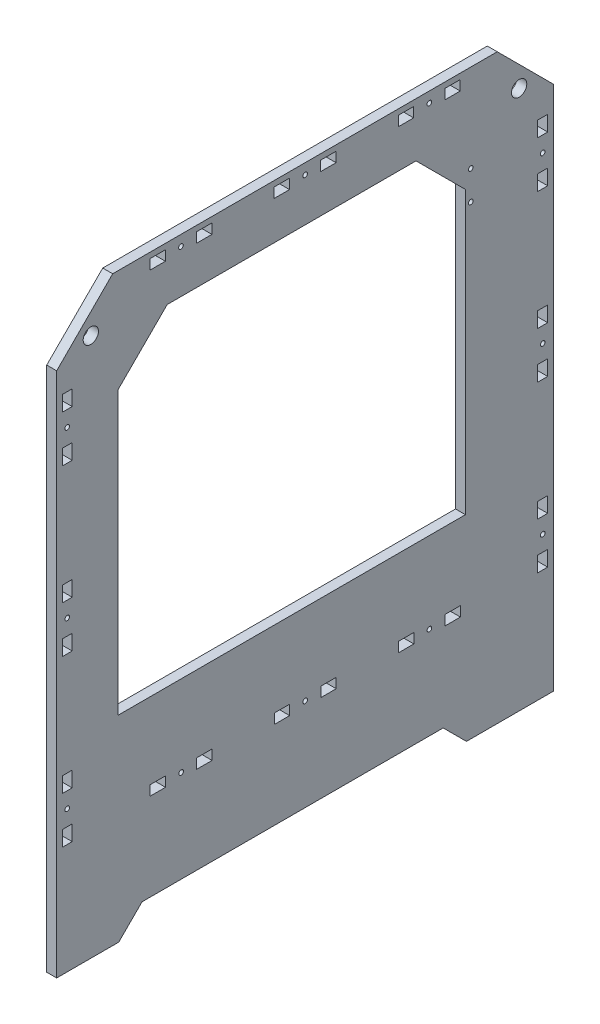
SolidWorks part; units mm, degrees
ref_plane "Front Plane" through (0, 0, 0) normal (0, 0, 1) x (1, 0, 0)
ref_plane "Top Plane" through (0, 0, 0) normal (0, 1, 0) x (1, 0, 0)
ref_plane "Right Plane" through (0, 0, 0) normal (1, 0, 0) x (0, 0, -1)
sketch "Sketch1" plane through (0, 0, 0) normal (1, 0, 0) x (0, 0, -1)
  line L1 (210.165, 41.2752) -> (-37.635, 41.2752)
  line L2 (-8.535, -255.9248) -> (-8.535, -262.3248) construction
  line L3 (181.365, 37.6752) -> (181.365, 31.2752) construction
  line L4 (151.365, 34.4752) -> (181.365, 34.4752) construction
  line L5 (151.465, -259.1248) -> (181.465, -259.1248) construction
  line L6 (71.465, -259.1248) -> (101.465, -259.1248) construction
  line L7 (-8.535, -259.1248) -> (21.465, -259.1248) construction
  line L9 (146.415, 37.6752) -> (146.415, 31.2752)
  line L20 (156.315, 37.6752) -> (156.315, 31.2752)
  line L21 (146.415, 37.6752) -> (156.315, 37.6752)
  line L22 (186.315, 37.6752) -> (176.415, 37.6752)
  line L23 (151.365, 37.6752) -> (151.365, 31.2752) construction
  line L24 (146.415, 31.2752) -> (156.315, 31.2752)
  line L25 (186.315, 31.2752) -> (176.415, 31.2752)
  line L26 (186.315, 37.6752) -> (186.315, 31.2752)
  line L27 (176.415, 37.6752) -> (176.415, 31.2752)
  line L28 (101.365, 37.6752) -> (101.365, 31.2752) construction
  line L29 (71.365, 34.4752) -> (101.365, 34.4752) construction
  line L30 (66.415, 37.6752) -> (66.415, 31.2752)
  line L31 (76.315, 37.6752) -> (76.315, 31.2752)
  line L32 (66.415, 37.6752) -> (76.315, 37.6752)
  line L33 (106.315, 37.6752) -> (96.415, 37.6752)
  line L34 (71.365, 37.6752) -> (71.365, 31.2752) construction
  line L35 (-73.735, -333.6748) -> (-73.735, 5.1752)
  line L37 (66.415, 31.2752) -> (76.315, 31.2752)
  line L38 (246.265, -333.6748) -> (246.265, 5.1752)
  line L42 (181.465, -255.9248) -> (181.465, -262.3248) construction
  line L43 (151.465, -255.9248) -> (151.465, -262.3248) construction
  line L45 (26.415, -255.9248) -> (26.415, -262.3248)
  line L46 (106.315, 31.2752) -> (96.415, 31.2752)
  line L48 (106.315, 37.6752) -> (106.315, 31.2752)
  line L50 (-73.735, 5.1752) -> (-37.635, 41.2752)
  line L51 (246.265, 5.1752) -> (210.165, 41.2752)
  line L52 (157.825, 6.5252) -> (189.675, -25.3248)
  line L53 (21.465, -255.9248) -> (21.465, -262.3248) construction
  line L54 (26.415, -255.9248) -> (16.515, -255.9248)
  line L55 (-3.585, -255.9248) -> (-3.585, -262.3248)
  line L56 (-2.5217, 6.5252) -> (-34.3717, -25.3248)
  line L57 (-13.485, -262.3248) -> (-3.585, -262.3248)
  line L59 (-2.5217, 6.5252) -> (157.825, 6.5252)
  line L60 (16.515, -255.9248) -> (16.515, -262.3248)
  line L61 (-13.485, -255.9248) -> (-3.585, -255.9248)
  line L62 (-13.485, -255.9248) -> (-13.485, -262.3248)
  line L63 (26.415, -262.3248) -> (16.515, -262.3248)
  line L64 (71.465, -255.9248) -> (71.465, -262.3248) construction
  line L65 (106.415, -255.9248) -> (106.415, -262.3248)
  line L67 (246.265, -333.6748) -> (190.325, -333.6748)
  line L68 (190.325, -333.6748) -> (175.325, -318.6748)
  line L69 (175.325, -318.6748) -> (-18.7217, -318.6748)
  line L70 (-18.7217, -318.6748) -> (-33.7217, -333.6748)
  line L71 (-33.7217, -333.6748) -> (-73.735, -333.6748)
  line L73 (96.415, 37.6752) -> (96.415, 31.2752)
  line L74 (21.365, 37.6752) -> (21.365, 31.2752) construction
  line L75 (101.465, -255.9248) -> (101.465, -262.3248) construction
  line L76 (106.415, -255.9248) -> (96.515, -255.9248)
  line L77 (-8.635, 34.4752) -> (21.365, 34.4752) construction
  line L78 (-13.585, 37.6752) -> (-13.585, 31.2752)
  line L79 (-3.685, 37.6752) -> (-3.685, 31.2752)
  line L80 (-13.585, 37.6752) -> (-3.685, 37.6752)
  line L81 (26.315, 37.6752) -> (16.415, 37.6752)
  line L82 (-8.635, 37.6752) -> (-8.635, 31.2752) construction
  line L83 (-13.585, 31.2752) -> (-3.685, 31.2752)
  line L84 (76.415, -255.9248) -> (76.415, -262.3248)
  line L85 (26.315, 31.2752) -> (16.415, 31.2752)
  line L86 (66.515, -262.3248) -> (76.415, -262.3248)
  line L87 (26.315, 37.6752) -> (26.315, 31.2752)
  line L88 (16.415, 37.6752) -> (16.415, 31.2752)
  line L94 (96.515, -255.9248) -> (96.515, -262.3248)
  line L95 (66.515, -255.9248) -> (76.415, -255.9248)
  line L96 (66.515, -255.9248) -> (66.515, -262.3248)
  line L97 (106.415, -262.3248) -> (96.515, -262.3248)
  line L107 (236.265, -40.1248) -> (242.665, -40.1248)
  line L108 (242.665, -40.1248) -> (242.665, -49.5248)
  line L110 (242.665, -49.5248) -> (236.265, -49.5248)
  line L111 (236.265, -40.1248) -> (236.265, -49.5248)
  line L141 (-34.3717, -206.8248) -> (-34.3717, -25.3248)
  line L178 (189.675, -206.8248) -> (-34.3717, -206.8248)
  line L179 (189.675, -206.8248) -> (189.675, -25.3248)
  line L237 (146.515, -255.9248) -> (146.515, -262.3248)
  line L238 (146.515, -262.3248) -> (156.415, -262.3248)
  line L242 (186.415, -255.9248) -> (176.515, -255.9248)
  line L244 (176.515, -255.9248) -> (176.515, -262.3248)
  line L249 (186.415, -255.9248) -> (186.415, -262.3248)
  line L253 (186.415, -262.3248) -> (176.515, -262.3248)
  line L257 (146.515, -255.9248) -> (156.415, -255.9248)
  line L258 (156.415, -255.9248) -> (156.415, -262.3248)
  circle A0 centre (6.365, 34.4752) radius 1.5
  circle A1 centre (86.365, 34.4752) radius 1.5
  circle A2 centre (166.365, 34.4752) radius 1.5
  circle A3 centre (86.465, -259.1248) radius 1.5
  circle A4 centre (166.465, -259.1248) radius 1.5
  circle A5 centre (6.465, -259.1248) radius 1.5
  circle A6 centre (239.465, -29.8248) radius 1.5
  circle A7 centre (239.465, -136.2248) radius 1.5
  circle A8 centre (239.465, -242.6248) radius 1.5
  circle A9 centre (-66.935, -242.6248) radius 1.5
  circle A10 centre (-66.935, -136.2248) radius 1.5
  circle A11 centre (-66.935, -29.8248) radius 1.5
  circle A13 centre (224.265, 13.8002) radius 4.925
  circle A14 centre (-51.735, 13.8002) radius 4.925
  circle A16 centre (193.115, -15.3248) radius 1.5
  circle A17 centre (193.115, -34.0748) radius 1.5
  dimension "D3" = 9.9
  dimension "D5" = 9.85
  dimension "D6" = 6.4
  dimension "D2" = 30
  dimension "D4" = 9.85
  dimension "D7" = 9.9
  dimension "D8" = 9.9
  dimension "D9" = 9.9
extrude "Boss-Extrude1" add sketch "Sketch1" along normal blind 6.4
sketch "Sketch2" plane through (6.4, 0, 0) normal (1, 0, 0) x (0, 0, -1)
  line L0 (-66.935, -257.6248) -> (-66.935, -227.6248) construction
  line L1 (-70.135, -227.6248) -> (-63.735, -227.6248) construction
  line L2 (-70.135, -257.6248) -> (-63.735, -257.6248) construction
  line L3 (-70.135, -262.5748) -> (-63.735, -262.5748)
  line L4 (-63.735, -262.5748) -> (-63.735, -252.6748)
  line L5 (-70.135, -222.6748) -> (-70.135, -232.5748)
  line L6 (-70.135, -232.5748) -> (-63.735, -232.5748)
  line L7 (-70.135, -222.6748) -> (-63.735, -222.6748)
  line L8 (-63.735, -222.6748) -> (-63.735, -232.5748)
  line L9 (-70.135, -262.5748) -> (-70.135, -252.6748)
  line L10 (-70.135, -252.6748) -> (-63.735, -252.6748)
  line L11 (-70.135, -116.2748) -> (-63.735, -116.2748)
  line L12 (-70.135, -151.2248) -> (-63.735, -151.2248) construction
  line L13 (-63.735, -156.1748) -> (-63.735, -146.2748)
  line L14 (-70.135, -146.2748) -> (-63.735, -146.2748)
  line L15 (-63.735, -116.2748) -> (-63.735, -126.1748)
  line L16 (-70.135, -121.2248) -> (-63.735, -121.2248) construction
  line L17 (-70.135, -116.2748) -> (-70.135, -126.1748)
  line L18 (-70.135, -156.1748) -> (-63.735, -156.1748)
  line L19 (-70.135, -156.1748) -> (-70.135, -146.2748)
  line L20 (-66.935, -151.2248) -> (-66.935, -121.2248) construction
  line L21 (-70.135, -126.1748) -> (-63.735, -126.1748)
  line L22 (-70.135, -9.8748) -> (-63.735, -9.8748)
  line L23 (-70.135, -44.8248) -> (-63.735, -44.8248) construction
  line L24 (-63.735, -49.7748) -> (-63.735, -39.8748)
  line L25 (-70.135, -39.8748) -> (-63.735, -39.8748)
  line L26 (-63.735, -9.8748) -> (-63.735, -19.7748)
  line L27 (-70.135, -14.8248) -> (-63.735, -14.8248) construction
  line L28 (-70.135, -9.8748) -> (-70.135, -19.7748)
  line L29 (-70.135, -49.7748) -> (-63.735, -49.7748)
  line L30 (-70.135, -49.7748) -> (-70.135, -39.8748)
  line L31 (-66.935, -44.8248) -> (-66.935, -14.8248) construction
  line L32 (-70.135, -19.7748) -> (-63.735, -19.7748)
  line L33 (236.265, -116.2748) -> (242.665, -116.2748)
  line L34 (236.265, -151.2248) -> (242.665, -151.2248) construction
  line L35 (242.665, -156.1748) -> (242.665, -146.2748)
  line L36 (236.265, -146.2748) -> (242.665, -146.2748)
  line L37 (242.665, -116.2748) -> (242.665, -126.1748)
  line L38 (236.265, -121.2248) -> (242.665, -121.2248) construction
  line L39 (236.265, -116.2748) -> (236.265, -126.1748)
  line L40 (236.265, -156.1748) -> (242.665, -156.1748)
  line L41 (236.265, -156.1748) -> (236.265, -146.2748)
  line L42 (239.465, -151.2248) -> (239.465, -121.2248) construction
  line L43 (236.265, -126.1748) -> (242.665, -126.1748)
  line L44 (236.265, -222.6748) -> (242.665, -222.6748)
  line L45 (236.265, -257.6248) -> (242.665, -257.6248) construction
  line L46 (242.665, -262.5748) -> (242.665, -252.6748)
  line L47 (236.265, -252.6748) -> (242.665, -252.6748)
  line L48 (242.665, -222.6748) -> (242.665, -232.5748)
  line L49 (236.265, -227.6248) -> (242.665, -227.6248) construction
  line L50 (236.265, -222.6748) -> (236.265, -232.5748)
  line L51 (236.265, -262.5748) -> (242.665, -262.5748)
  line L52 (236.265, -262.5748) -> (236.265, -252.6748)
  line L53 (239.465, -257.6248) -> (239.465, -227.6248) construction
  line L54 (236.265, -232.5748) -> (242.665, -232.5748)
  line L55 (236.265, -9.8748) -> (242.665, -9.8748)
  line L56 (236.265, -44.8248) -> (242.665, -44.8248) construction
  line L57 (242.665, -49.7748) -> (242.665, -39.8748)
  line L58 (236.265, -39.8748) -> (242.665, -39.8748)
  line L59 (242.665, -9.8748) -> (242.665, -19.7748)
  line L60 (236.265, -14.8248) -> (242.665, -14.8248) construction
  line L61 (236.265, -9.8748) -> (236.265, -19.7748)
  line L62 (236.265, -49.7748) -> (242.665, -49.7748)
  line L63 (236.265, -49.7748) -> (236.265, -39.8748)
  line L64 (239.465, -44.8248) -> (239.465, -14.8248) construction
  line L65 (236.265, -19.7748) -> (242.665, -19.7748)
  circle A0 centre (-66.935, -242.6248) radius 1.5
  circle A1 centre (-66.935, -136.2248) radius 1.5
  circle A2 centre (-66.935, -29.8248) radius 1.5
  circle A3 centre (239.465, -136.2248) radius 1.5
  circle A4 centre (239.465, -242.6248) radius 1.5
  circle A5 centre (239.465, -29.8248) radius 1.5
  dimension "D22" = 9.9
  dimension "D23" = 6.4
extrude "Cut-Extrude1" cut sketch "Sketch2" against normal through all
